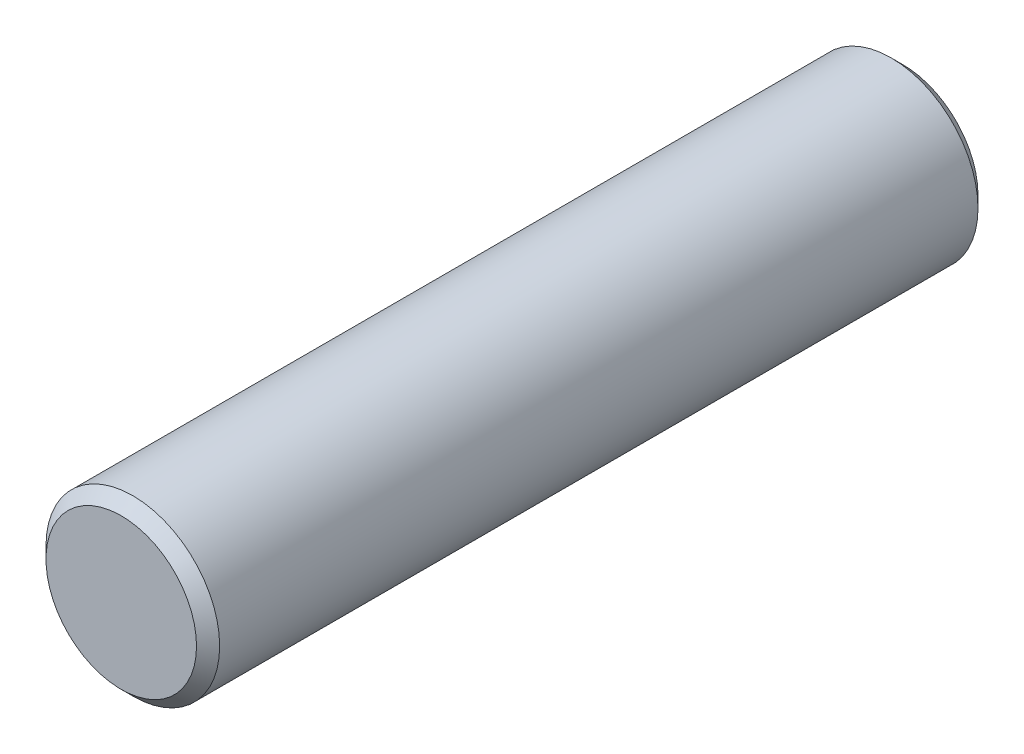
SolidWorks part; units mm, degrees
ref_plane "Ön Düzlem" through (0, 0, 0) normal (0, 0, 1) x (1, 0, 0)
ref_plane "Üst Düzlem" through (0, 0, 0) normal (0, 1, 0) x (1, 0, 0)
ref_plane "Sağ Düzlem" through (0, 0, 0) normal (1, 0, 0) x (0, 0, -1)
sketch "Sketch1" plane through (0, 0, 0) normal (0, 0, 1) x (1, 0, 0)
  circle A0 centre (0, 0) radius 1.5
extrude "Boss-Extrude1" add sketch "Sketch1" along normal mid plane 13.5
chamfer "Chamfer1" distance 0.2 angle 45 2 edges at (1.5, 0, -6.75) (1.5, 0, 6.75)
scale "Scale1" scale about centroid uniform scaling yes scale factor 1.5
